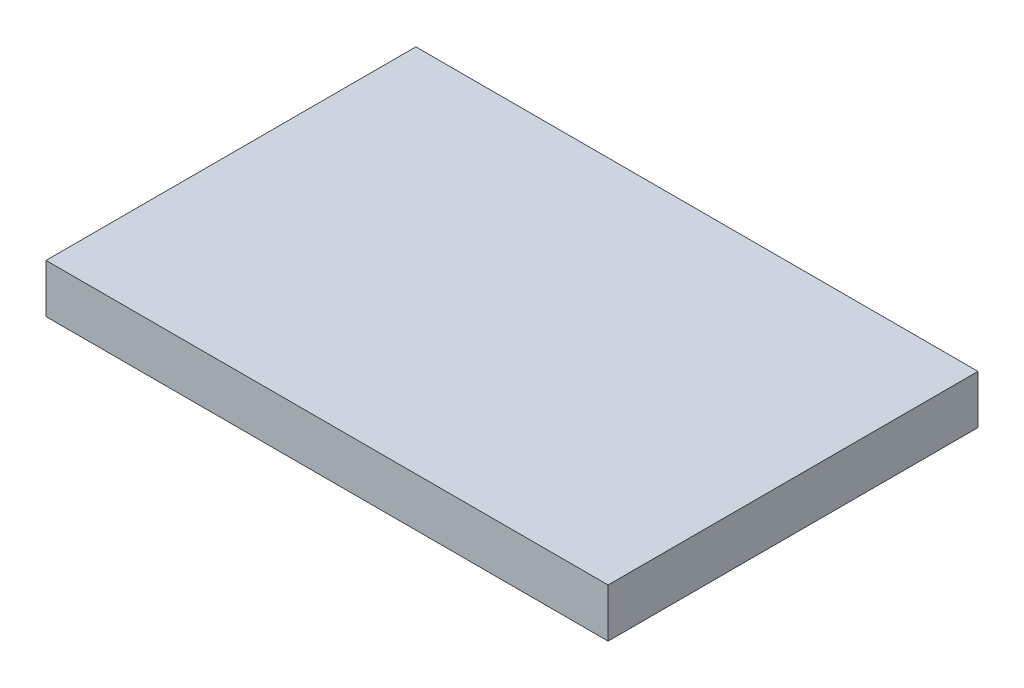
SolidWorks part; units mm, degrees
ref_plane "Plan de face" through (0, 0, 0) normal (0, 0, 1) x (1, 0, 0)
ref_plane "Plan de dessus" through (0, 0, 0) normal (0, 1, 0) x (1, 0, 0)
ref_plane "Plan de droite" through (0, 0, 0) normal (1, 0, 0) x (0, 0, -1)
sketch "Esquisse1" plane through (0, 0, 0) normal (0, 1, 0) x (1, 0, 0)
  line L1 (23.1, -15.2) -> (-23.1, -15.2)
  line L2 (23.1, -15.2) -> (23.1, 15.2)
  line L3 (23.1, 15.2) -> (-23.1, 15.2)
  line L4 (-23.1, -15.2) -> (-23.1, 15.2)
  line L5 (23.1, -15.2) -> (-23.1, 15.2) construction
  line L6 (23.1, 15.2) -> (-23.1, -15.2) construction
  point P0 (0, 0)
  dimension "D1" = 46.2
  dimension "D2" = 30.4
extrude "Boss.-Extru.1" add sketch "Esquisse1" along normal blind 4
